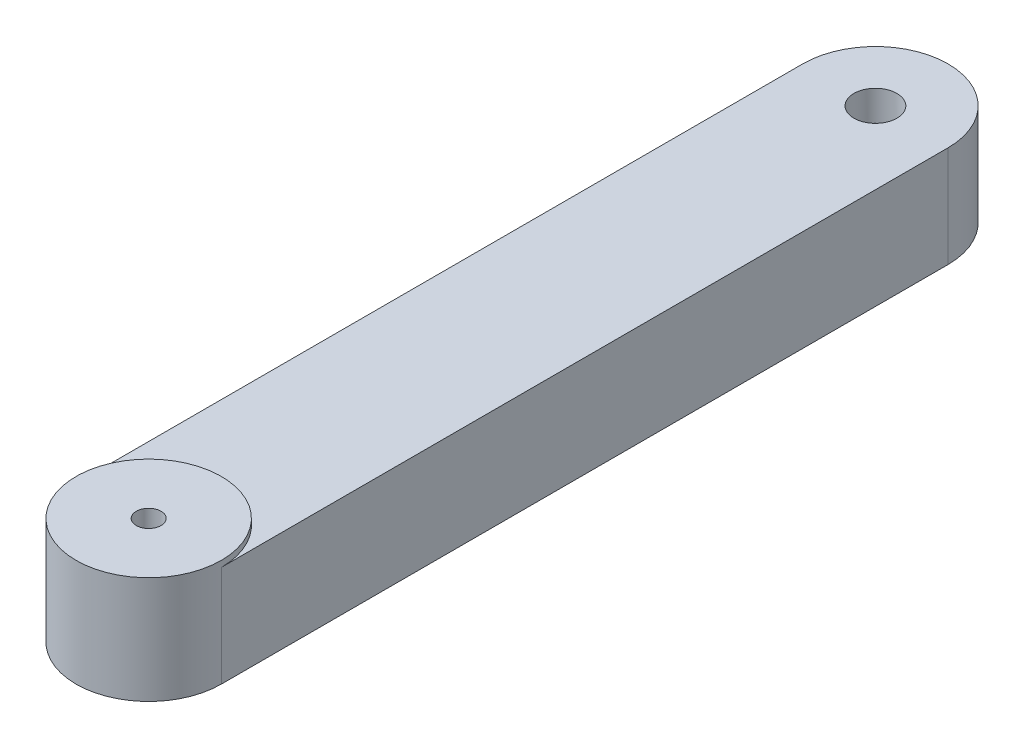
SolidWorks part; units mm, degrees
material "PLA Infill"
ref_plane "Front Plane" through (0, 0, 0) normal (0, 0, 1) x (1, 0, 0)
ref_plane "Top Plane" through (0, 0, 0) normal (0, 1, 0) x (1, 0, 0)
ref_plane "Right Plane" through (0, 0, 0) normal (1, 0, 0) x (0, 0, -1)
sketch "Sketch1" plane through (0, 0, 0) normal (0, 1, 0) x (1, 0, 0)
  line L0 (0, -60) -> (0, 60) construction
  line L1 (-12, -60) -> (-12, 60)
  line L2 (12, -60) -> (12, 60)
  arc A0 (-12, -60) -> (12, -60) centre (0, -60) ccw
  arc A1 (12, 60) -> (-12, 60) centre (0, 60) ccw
  circle A2 centre (0, 60) radius 2.05
  circle A3 centre (0, -60) radius 2.05
  point P2 (0, 0)
  dimension "D1" = 12
  dimension "D3" = 4.1
  dimension "D2" = 120
extrude "Boss-Extrude1" add sketch "Sketch1" along normal blind 17.7
sketch "Sketch2" plane through (0, 17.7, 0) normal (0, 1, 0) x (1, 0, 0)
  circle A0 centre (0, 60) radius 3.55
  dimension "D1" = 7.1
extrude "Cut-Extrude1" cut sketch "Sketch2" against normal blind 6
sketch "Sketch3" plane through (0, 17.7, 0) normal (0, 1, 0) x (1, 0, 0)
  line L0 (12, -60) -> (12, 60) construction
  line L1 (-12, 60) -> (-12, -60) construction
  line L2 (12, -60) -> (12, 60)
  line L3 (-12, 60) -> (-12, -60)
  circle A0 centre (0, -60) radius 12 construction
  arc A1 (12, 60) -> (-12, 60) centre (0, 60) ccw construction
  arc A2 (12, 60) -> (-12, 60) centre (0, 60) ccw
  arc A3 (-12, -60) -> (12, -60) centre (0, -60) cw
  dimension "D1" = 24
extrude "Cut-Extrude2" cut sketch "Sketch3" against normal blind 1
